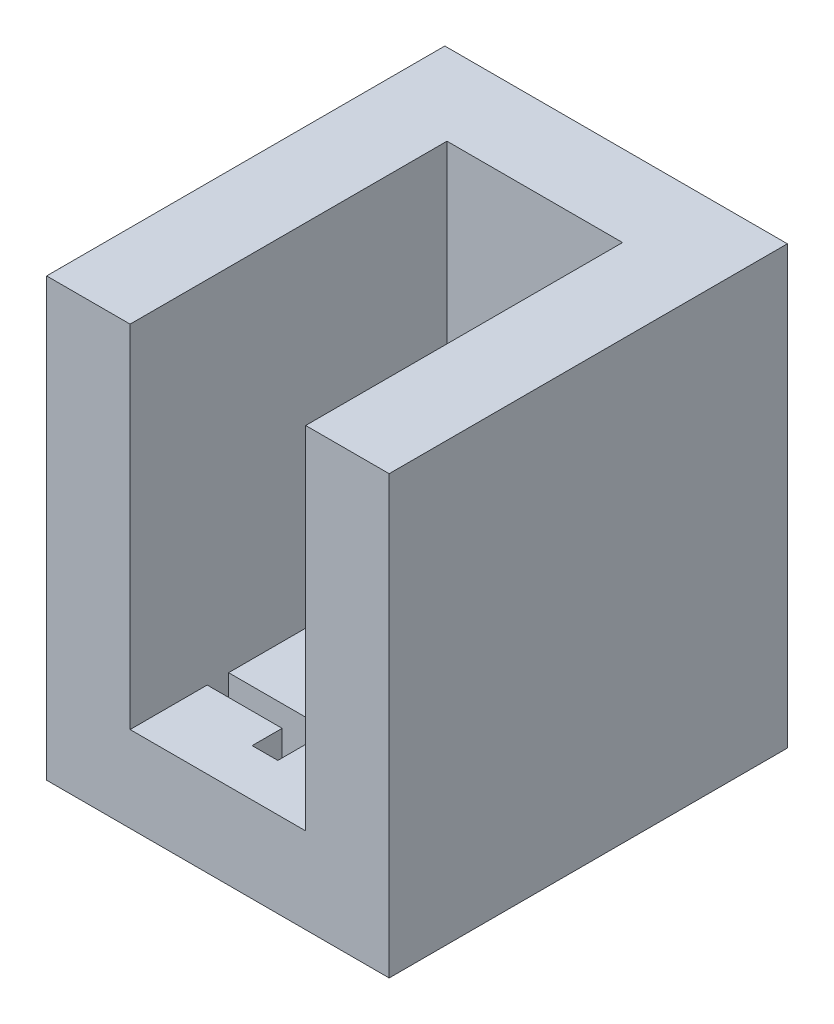
SolidWorks part; units mm, degrees
ref_plane "Front Plane" through (0, 0, 0) normal (0, 0, 1) x (1, 0, 0)
ref_plane "Top Plane" through (0, 0, 0) normal (0, 1, 0) x (1, 0, 0)
ref_plane "Right Plane" through (0, 0, 0) normal (1, 0, 0) x (0, 0, -1)
sketch "Sketch1" plane through (0, 0, 0) normal (0, 1, 0) x (1, 0, 0)
  line L1 (-20, -23.25) -> (20, -23.25)
  line L2 (-20, -23.25) -> (-20, 23.25)
  line L3 (-20, 23.25) -> (20, 23.25)
  line L4 (20, -23.25) -> (20, 23.25)
  line L5 (-20, -23.25) -> (20, 23.25) construction
  line L6 (-20, 23.25) -> (20, -23.25) construction
  point P0 (0, 0)
  dimension "D1" = 46.5
  dimension "D2" = 40
extrude "Boss-Extrude1" add sketch "Sketch1" along normal blind 51
sketch "Sketch2" plane through (0, 51, 0) normal (0, 1, 0) x (1, 0, 0)
  line L0 (-20, -23.25) -> (20, -23.25) construction
  line L1 (-10.25, 13.75) -> (10.25, 13.75)
  line L2 (-10.25, 13.75) -> (-10.25, -23.25)
  line L3 (-10.25, -23.25) -> (10.25, -23.25)
  line L4 (10.25, 13.75) -> (10.25, -23.25)
  line L5 (20, -23.25) -> (20, 23.25) construction
  line L6 (-20, 23.25) -> (-20, -23.25) construction
  line L7 (20, 23.25) -> (-20, 23.25) construction
  dimension "D1" = 9.75
  dimension "D2" = 9.75
  dimension "D3" = 9.5
extrude "Cut-Extrude1" cut sketch "Sketch2" against normal blind 41
sketch "Sketch3" plane through (0, 10, 0) normal (0, 1, 0) x (1, 0, 0)
  line L0 (-10.25, 13.75) -> (-10.25, -23.25) construction
  line L1 (-10.25, -11.75) -> (10.25, -11.75)
  line L2 (-10.25, -11.75) -> (-10.25, -14.25)
  line L3 (-10.25, -14.25) -> (-1.5, -14.25)
  line L4 (10.25, -11.75) -> (10.25, -14.25)
  line L5 (10.25, -23.25) -> (10.25, 13.75) construction
  line L6 (10.25, 13.75) -> (-10.25, 13.75) construction
  line L7 (1.5, -14.25) -> (10.25, -14.25)
  line L9 (-1.5, -14.25) -> (-1.5, -17.75)
  line L10 (-1.5, -17.75) -> (1.5, -17.75)
  line L11 (1.5, -14.25) -> (1.5, -17.75)
  dimension "D1" = 25.5
  dimension "D2" = 2.5
  dimension "D3" = 3
  dimension "D4" = 3.5
  dimension "D5" = 8.75
extrude "Cut-Extrude2" cut sketch "Sketch3" against normal blind 8.5 contours L7 L4 L1 L2 L3 L9 L10 L11
